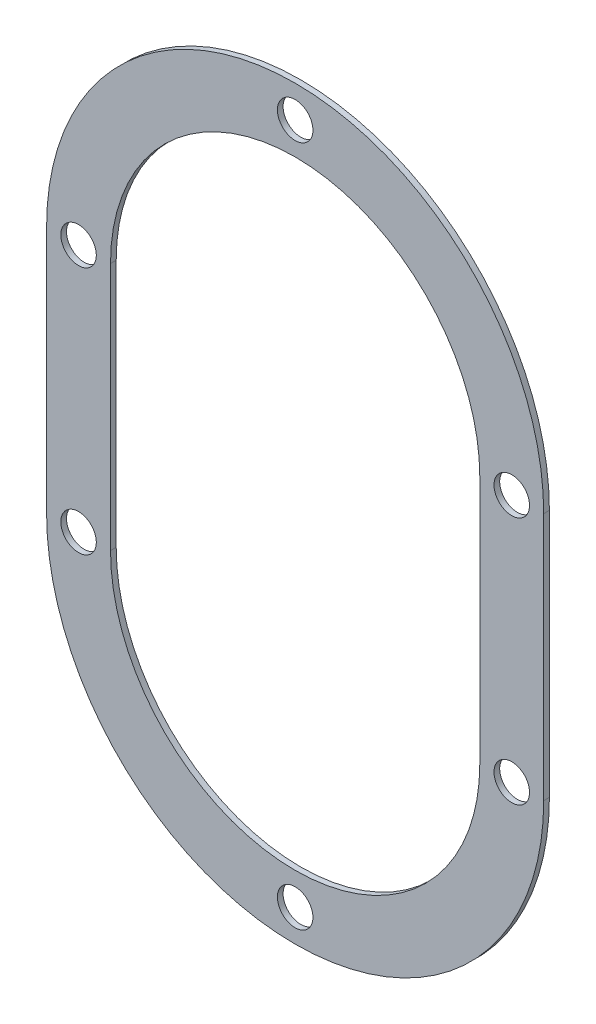
SolidWorks part; units mm, degrees
ref_plane "Front Plane" through (0, 0, 0) normal (0, 0, 1) x (1, 0, 0)
ref_plane "Top Plane" through (0, 0, 0) normal (0, 1, 0) x (1, 0, 0)
ref_plane "Right Plane" through (0, 0, 0) normal (1, 0, 0) x (0, 0, -1)
sketch "Sketch1" plane through (0, 0, 0) normal (0, 0, 1) x (1, 0, 0)
  line L0 (-35, 0) -> (-35, -35)
  line L1 (35, 0) -> (35, -35)
  line L2 (-26, 0) -> (-26, -35)
  line L3 (26, 0) -> (26, -35)
  line L4 (0, 35) -> (0, 26) construction
  line L5 (0, 26) -> (0, -61) construction
  line L6 (0, -61) -> (0, -70) construction
  line L7 (-35, 0) -> (-26, 0) construction
  line L8 (-35, -35) -> (-26, -35) construction
  line L9 (26, 0) -> (35, 0) construction
  line L10 (26, -35) -> (35, -35) construction
  arc A0 (35, 0) -> (-35, 0) centre (0, 0) ccw
  arc A1 (-35, -35) -> (35, -35) centre (0, -35) ccw
  arc A2 (26, 0) -> (-26, 0) centre (0, 0) ccw
  arc A3 (-26, -35) -> (26, -35) centre (0, -35) ccw
  circle A4 centre (0, 0) radius 30.5 construction
  circle A5 centre (0, -35) radius 30.5 construction
  circle A6 centre (-30.5, 0) radius 2.5
  circle A7 centre (0, 30.5) radius 2.5
  circle A8 centre (30.5, 0) radius 2.5
  circle A9 centre (30.5, -35) radius 2.5
  circle A10 centre (0, -65.5) radius 2.5
  circle A11 centre (-30.5, -35) radius 2.5
  point P15 (-30.5, 0)
  point P18 (-30.5, -35)
  dimension "D2" = 70
  dimension "D4" = 5
  dimension "D1" = 35
  dimension "D3" = 9
extrude "Boss-Extrude1" add sketch "Sketch1" along normal blind 0.8
scale "Scale1" scale about centroid uniform scaling yes scale factor 0.317565
